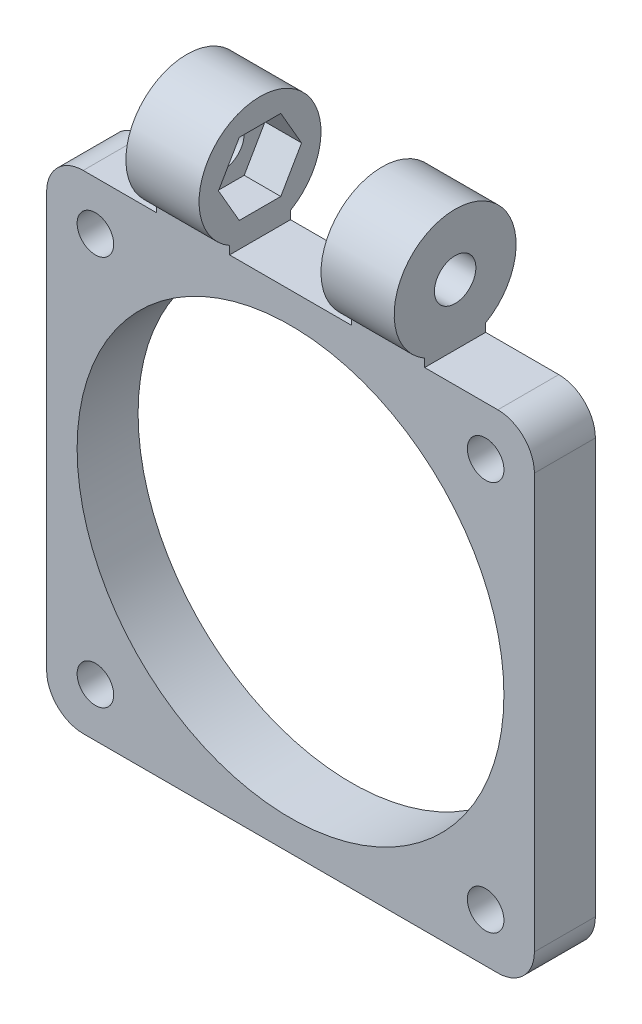
SolidWorks part; units mm, degrees
ref_plane "Спереди" through (0, 0, 0) normal (0, 0, 1) x (1, 0, 0)
ref_plane "Сверху" through (0, 0, 0) normal (0, 1, 0) x (1, 0, 0)
ref_plane "Справа" through (0, 0, 0) normal (1, 0, 0) x (0, 0, -1)
sketch "Эскиз1" plane through (0, 0, 0) normal (0, 0, 1) x (1, 0, 0)
  line L1 (-20, 20) -> (20, 20)
  line L2 (-20, 20) -> (-20, -20)
  line L3 (-20, -20) -> (20, -20)
  line L4 (20, 20) -> (20, -20)
  line L5 (-20, 20) -> (20, -20) construction
  line L6 (-20, -20) -> (20, 20) construction
  point P0 (0, 0)
  dimension "D1" = 40
  dimension "D2" = 40
extrude "Бобышка-Вытянуть1" add sketch "Эскиз1" along normal blind 5
sketch "Эскиз2" plane through (0, 0, 5) normal (0, 0, 1) x (1, 0, 0)
  line L0 (0, 0) -> (-16, 0)
  line L1 (-16, 0) -> (-16, 16)
  line L2 (0, 0) -> (0, 5.2462)
  circle A0 centre (0, 0) radius 16
  circle A1 centre (-16, 16) radius 1.5
  circle A2 centre (16, 16) radius 1.5
  circle A3 centre (16, -16) radius 1.5
  circle A4 centre (-16, -16) radius 1.5
  dimension "D3" = 3
  dimension "D1" = 16
  dimension "D2" = 16
extrude "Вырез-Вытянуть1" cut sketch "Эскиз2" against normal through all
sketch "Эскиз3" plane through (0, 20, 0) normal (0, 1, 0) x (1, 0, 0)
  line L0 (-5, -5) -> (-5, 0)
  line L1 (0, -5) -> (0, 0)
  line L2 (20, -5) -> (-20, -5) construction
  line L3 (0, 0) -> (-11, 0)
  line L4 (20, 0) -> (-20, 0) construction
  line L5 (-11, 0) -> (-11, -5)
  line L6 (-11, -5) -> (-5, -5)
  line L7 (11, -5) -> (5, -5)
  line L8 (11, 0) -> (11, -5)
  line L9 (5, -5) -> (5, 0)
  line L10 (5, 0) -> (11, 0)
  line M4 (20, 0) -> (-20, 0)
  line M6 (-20, -5) -> (20, -5)
  dimension "D1" = 11
  dimension "D2" = 6
extrude "Бобышка-Вытянуть2" add sketch "Эскиз3" along normal blind 10 contours L5 L0 M4 M6 | L9 L8 M6 M4
sketch "Эскиз4" plane through (-11, 0, 0) normal (-1, 0, 0) x (0, 0, 1)
  line L0 (2.5, 30) -> (2.5, 25)
  line L1 (0, 30) -> (5, 30) construction
  circle A0 centre (2.5, 25) radius 3
  dimension "D1" = 6
  dimension "D2" = 5
extrude "Бобышка-Вытянуть3" add sketch "Эскиз4" against normal blind 6
sketch "Эскиз5" plane through (11, 0, 0) normal (1, 0, 0) x (0, 0, -1)
  circle A0 centre (-2.5, 25) radius 3
  dimension "D1" = 6
extrude "Бобышка-Вытянуть4" add sketch "Эскиз5" against normal blind 6
sketch "Эскиз6" plane through (11, 0, 0) normal (1, 0, 0) x (0, 0, -1)
  line L0 (-5, 30) -> (0, 30)
  line L1 (0, 30) -> (0, 26.6583)
  circle A0 centre (-2.5, 25) radius 3
  line M3 (0, 26.6583) -> (0, 30)
  line M4 (0, 30) -> (-5, 30)
  line M5 (-5, 30) -> (-5, 26.6583)
extrude "Вырез-Вытянуть2" cut sketch "Эскиз6" against normal through all contours A0 M3 M4 M5
sketch "Эскиз7" plane through (-11, 0, 0) normal (-1, 0, 0) x (0, 0, 1)
  circle A0 centre (2.5, 25) radius 1.5
extrude "Вырез-Вытянуть3" cut sketch "Эскиз7" against normal through all
sketch "Эскиз9" plane through (-11, 0, 0) normal (-1, 0, 0) x (0, 0, 1)
  circle A0 centre (2.5, 25) radius 4
  dimension "D1" = 8
extrude "Бобышка-Вытянуть5" add sketch "Эскиз9" against normal blind 6
sketch "Эскиз10" plane through (11, 0, 0) normal (1, 0, 0) x (0, 0, -1)
  circle A0 centre (-2.5, 25) radius 4
extrude "Бобышка-Вытянуть6" add sketch "Эскиз10" against normal blind 6
sketch "Эскиз11" plane through (11, 0, 0) normal (1, 0, 0) x (0, 0, -1)
  circle A0 centre (-2.5, 25) radius 1.5
  dimension "D1" = 3
extrude "Вырез-Вытянуть4" cut sketch "Эскиз11" against normal through all
sketch "Эскиз12" plane through (-5, 0, 0) normal (1, 0, 0) x (0, 0, -1)
  line L0 (-5, 20) -> (0, 20) construction
  line L1 (-0.9123, 22.25) -> (0.6754, 25)
  line L2 (0.6754, 25) -> (-0.9123, 27.75)
  line L3 (-0.9123, 27.75) -> (-4.0877, 27.75)
  line L4 (-4.0877, 27.75) -> (-5.6754, 25)
  line L5 (-5.6754, 25) -> (-4.0877, 22.25)
  line L6 (-4.0877, 22.25) -> (-0.9123, 22.25)
  circle A0 centre (-2.5, 25) radius 2.75 construction
  dimension "D1" = 5.5
extrude "Вырез-Вытянуть5" cut sketch "Эскиз12" against normal blind 3 and the other way blind 13
fillet "Скругление1" radius 3 4 edges at (20, -20, 2.5) (-20, -20, 2.5) (-20, 20, 2.5) (20, 20, 2.5)
sketch "Эскиз13" plane through (-5, 0, 0) normal (1, 0, 0) x (0, 0, -1)
  line L1 (-4.1743, 22.1) -> (-0.8257, 22.1)
  line L2 (-0.8257, 22.1) -> (0.8486, 25)
  line L3 (0.8486, 25) -> (-0.8257, 27.9)
  line L4 (-0.8257, 27.9) -> (-4.1743, 27.9)
  line L5 (-4.1743, 27.9) -> (-5.8486, 25)
  line L6 (-5.8486, 25) -> (-4.1743, 22.1)
  circle A0 centre (-2.5, 25) radius 2.9 construction
  dimension "D1" = 5.8
extrude "Вырез-Вытянуть6" cut sketch "Эскиз13" against normal up to vertex (3 mm away) up to point (-8, 27.75, 0.9123)
sketch "Эскиз14" plane through (5, 0, 0) normal (-1, 0, 0) x (0, 0, 1)
  line L1 (4.1743, 22.1) -> (5.8486, 25)
  line L2 (5.8486, 25) -> (4.1743, 27.9)
  line L3 (4.1743, 27.9) -> (0.8257, 27.9)
  line L4 (0.8257, 27.9) -> (-0.8486, 25)
  line L5 (-0.8486, 25) -> (0.8257, 22.1)
  line L6 (0.8257, 22.1) -> (4.1743, 22.1)
  circle A0 centre (2.5, 25) radius 2.9 construction
  dimension "D1" = 5.8
extrude "Вырез-Вытянуть7" cut sketch "Эскиз14" against normal up to vertex (3 mm away) up to point (8, 25, -0.6754)
sketch "Эскиз15" plane through (-11, 0, 0) normal (-1, 0, 0) x (0, 0, 1)
  circle A0 centre (2.5, 25) radius 1.65
  dimension "D1" = 3.3
extrude "Вырез-Вытянуть8" cut sketch "Эскиз15" against normal through all
sketch "Эскиз16" plane through (-11, 0, 0) normal (-1, 0, 0) x (0, 0, 1)
  circle A0 centre (2.5, 25) radius 5
  dimension "D1" = 10
extrude "Бобышка-Вытянуть7" add sketch "Эскиз16" against normal blind 6
sketch "Эскиз17" plane through (11, 0, 0) normal (1, 0, 0) x (0, 0, -1)
  circle A0 centre (-2.5, 25) radius 5
extrude "Бобышка-Вытянуть8" add sketch "Эскиз17" against normal blind 6
sketch "Эскиз18" plane through (11, 0, 0) normal (1, 0, 0) x (0, 0, -1)
  circle A0 centre (-2.5, 25) radius 1.7
  dimension "D1" = 3.4
extrude "Вырез-Вытянуть9" cut sketch "Эскиз18" against normal through all
sketch "Эскиз19" plane through (-5, 0, 0) normal (1, 0, 0) x (0, 0, -1)
  line L0 (-5, 20) -> (0, 20) construction
  line L1 (-4.2032, 22.05) -> (-0.7968, 22.05)
  line L2 (-0.7968, 22.05) -> (0.9064, 25)
  line L3 (0.9064, 25) -> (-0.7968, 27.95)
  line L4 (-0.7968, 27.95) -> (-4.2032, 27.95)
  line L5 (-4.2032, 27.95) -> (-5.9064, 25)
  line L6 (-5.9064, 25) -> (-4.2032, 22.05)
  circle A0 centre (-2.5, 25) radius 2.95 construction
  dimension "D1" = 5.9
extrude "Вырез-Вытянуть10" cut sketch "Эскиз19" against normal blind 3 and the other way blind 13
sketch "Эскиз20" plane through (0, 0, 5) normal (0, 0, 1) x (1, 0, 0)
  circle A0 centre (0, 0) radius 17.5
  dimension "D1" = 35
extrude "Вырез-Вытянуть11" cut sketch "Эскиз20" against normal through all
